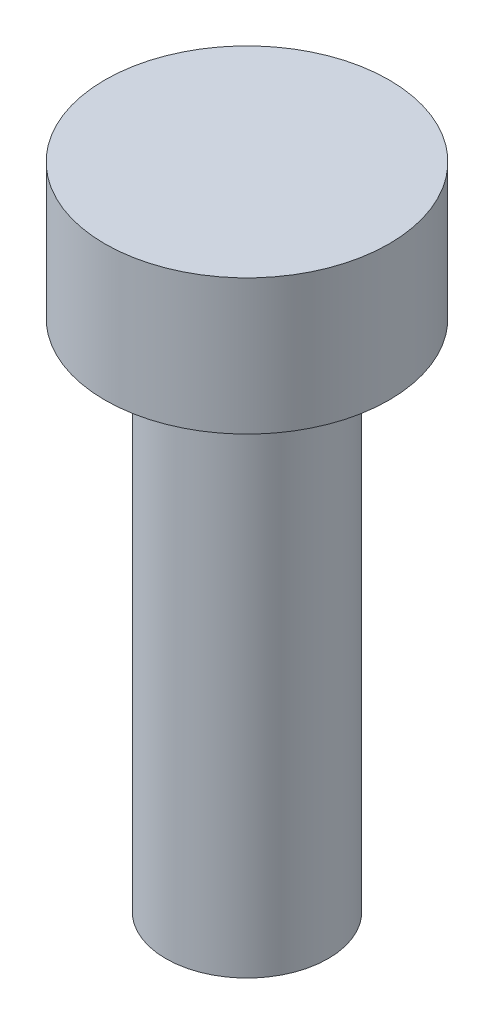
SolidWorks part; units mm, degrees
ref_plane "Front Plane" through (0, 0, 0) normal (0, 0, 1) x (1, 0, 0)
ref_plane "Top Plane" through (0, 0, 0) normal (0, 1, 0) x (1, 0, 0)
ref_plane "Right Plane" through (0, 0, 0) normal (1, 0, 0) x (0, 0, -1)
sketch "Sketch1" plane through (0, 0, 0) normal (0, 1, 0) x (1, 0, 0)
  circle A0 centre (0, 0) radius 2.667
  dimension "D1" = 5.334
extrude "Boss-Extrude1" add sketch "Sketch1" along normal blind 2.54
sketch "Sketch2" plane through (0, 0, 0) normal (0, -1, 0) x (-1, 0, 0)
  circle A0 centre (0, 0) radius 1.524
  dimension "D1" = 3.048
extrude "Boss-Extrude2" add sketch "Sketch2" along normal blind 9.652
